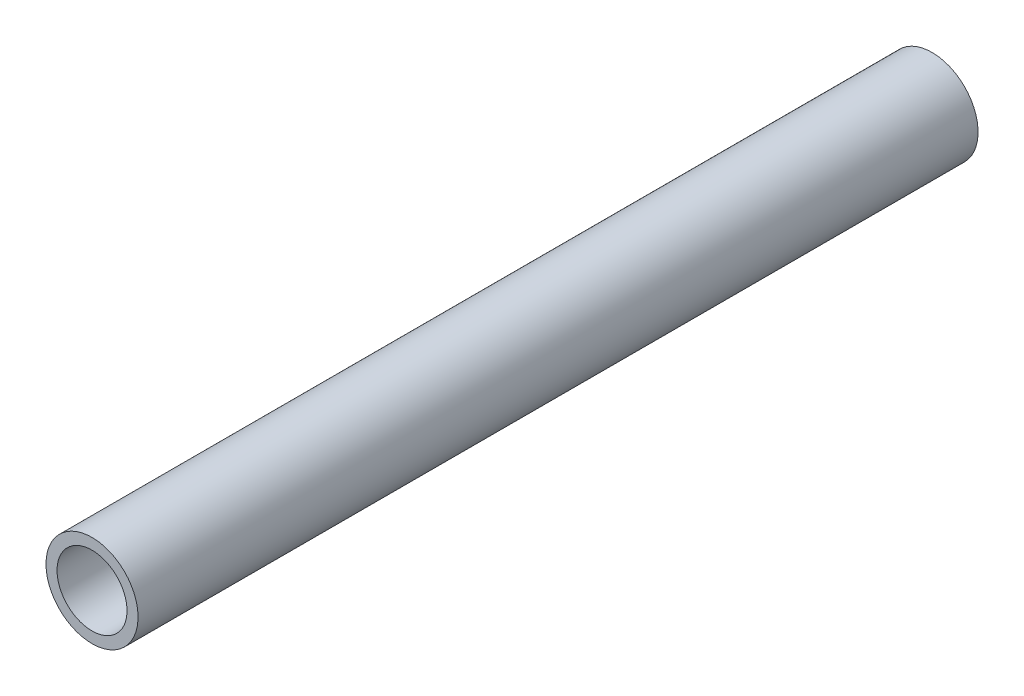
SolidWorks part; units mm, degrees
material "Plain Carbon Steel"
ref_plane "Front Plane" through (0, 0, 0) normal (0, 0, 1) x (1, 0, 0)
ref_plane "Top Plane" through (0, 0, 0) normal (0, 1, 0) x (1, 0, 0)
ref_plane "Right Plane" through (0, 0, 0) normal (1, 0, 0) x (0, 0, -1)
sketch "Sketch1" plane through (0, 0, 0) normal (0, 0, 1) x (1, 0, 0)
  circle A0 centre (0, 0) radius 12.7
  circle A1 centre (0, 0) radius 16.7005
extrude "Boss-Extrude1" add sketch "Sketch1" along normal blind 304.8
